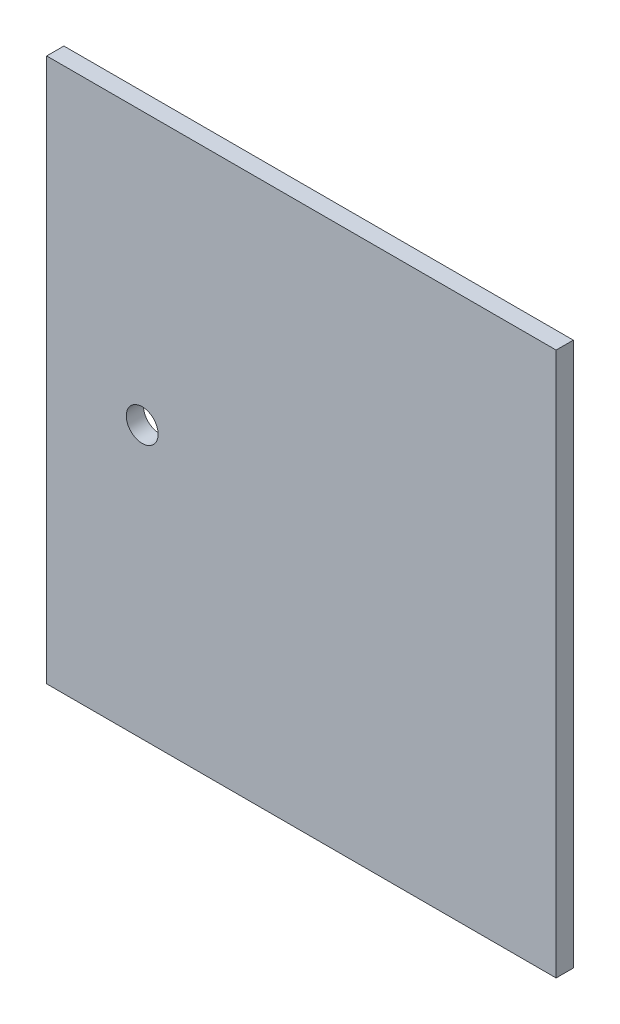
SolidWorks part; units mm, degrees
material "Acrílico (Impacto medio-alto)"
ref_plane "Alzado" through (0, 0, 0) normal (0, 0, 1) x (1, 0, 0)
ref_plane "Planta" through (0, 0, 0) normal (0, 1, 0) x (1, 0, 0)
ref_plane "Vista lateral" through (0, 0, 0) normal (1, 0, 0) x (0, 0, -1)
sketch "Croquis1" plane through (0, 0, 0) normal (0, 0, 1) x (1, 0, 0)
  line L1 (-82.7, 0) -> (-2.7, 0)
  line L2 (-82.7, 0) -> (-82.7, 85.4)
  line L3 (-82.7, 85.4) -> (-2.7, 85.4)
  line L4 (-2.7, 0) -> (-2.7, 85.4)
extrude "Saliente-Extruir1" add sketch "Croquis1" along normal blind 2.7
sketch "Croquis2" plane through (0, 0, 2.7) normal (0, 0, 1) x (1, 0, 0)
  line L0 (-42.7, 0) -> (-42.7, 85.4) construction
  line L1 (-82.7, 0) -> (-2.7, 0) construction
  line L2 (-2.7, 85.4) -> (-82.7, 85.4) construction
  line L3 (-82.7, 42.7) -> (-42.7, 42.7) construction
  line L4 (-82.7, 85.4) -> (-82.7, 0) construction
  circle A0 centre (-67.7, 42.7) radius 2.5
  dimension "D1" = 5
  dimension "D2" = 15
extrude "Cortar-Extruir1" cut sketch "Croquis2" against normal blind 2.7
